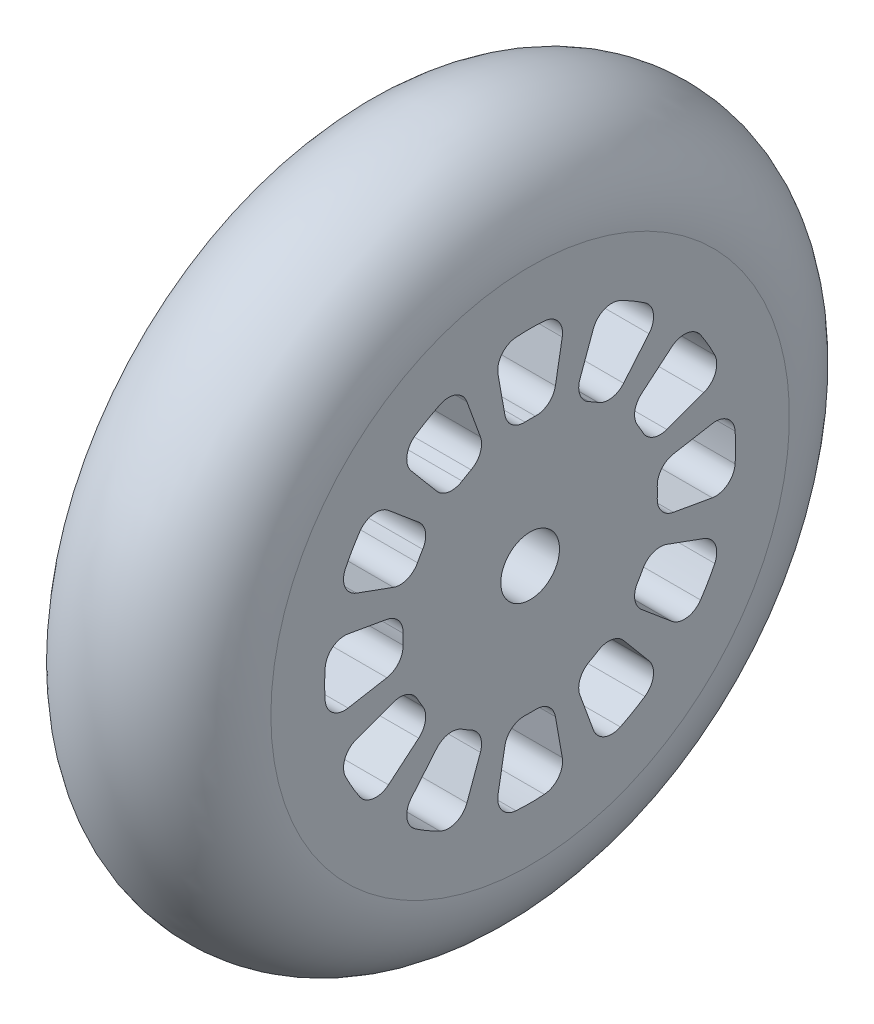
SolidWorks part; units mm, degrees
ref_plane "Front Plane" through (0, 0, 0) normal (0, 0, 1) x (1, 0, 0)
ref_plane "Top Plane" through (0, 0, 0) normal (0, 1, 0) x (1, 0, 0)
ref_plane "Right Plane" through (0, 0, 0) normal (1, 0, 0) x (0, 0, -1)
sketch "Sketch3" plane through (0, 0, 0) normal (0, 0, 1) x (1, 0, 0)
  line L0 (11.8162, 203.7798) -> (97.9345, 203.7798) construction
  line L1 (9.5, 0) -> (-9.5, 0) construction
  line L2 (9.5, 0) -> (9.5, 26.5)
  line L3 (-9.5, 26.5) -> (-9.5, 0)
  line L4 (9.5, 0) -> (-9.5, 0)
  arc A0 (9.5, 26.5) -> (-9.5, 26.5) centre (0, 26.5) ccw
  point P8 (0, 36)
  dimension "D1" = 19
  dimension "D2" = 36
ref_axis "Axis1" through (-15.0817, 0, 0) along (1, 0, 0)
revolve "Revolve1" add sketch "Sketch3" angle 360 about axis through (-15.0817, 0, 0) along (1, 0, 0)
sketch "Sketch5" plane through (0, 0, 0) normal (1, 0, 0) x (0, 0, -1)
  line L0 (42.6541, 201.0631) -> (357.9874, 201.0631) construction
  circle A0 centre (0, 0) radius 3
  dimension "D1" = 6
extrude "Cut-Extrude1" cut sketch "Sketch5" against normal up to next and the other way up to next
sketch "Sketch6" plane through (0, 0, 0) normal (1, 0, 0) x (0, 0, -1)
  line L0 (-3.6466, 20.681) -> (-2.2574, 12.8025)
  line L1 (3.6466, 20.681) -> (2.2574, 12.8025)
  line L2 (0, 21) -> (0, 13) construction
  circle A0 centre (0, 0) radius 13 construction
  circle A1 centre (0, 0) radius 21 construction
  arc A2 (-3.6466, 20.681) -> (3.6466, 20.681) centre (0, 0) cw
  arc A3 (-2.2574, 12.8025) -> (2.2574, 12.8025) centre (0, 0) cw
  dimension "D1" = 26
  dimension "D2" = 42
  dimension "D3" = 20
extrude "Cut-Extrude2" cut sketch "Sketch6" against normal through all and the other way through all
fillet "Fillet1" radius 2 4 edges at (0, 12.8025, 2.2574) (0, 12.8025, -2.2574) (0, 20.681, -3.6466) (0, 20.681, 3.6466)
pattern_circular "CirPattern2" count 12 over 360 about axis through (0, 0, 0) along (1, 0, 0) of "Fillet1", "Cut-Extrude2"
sketch "Sketch7" plane through (0, 0, 0) normal (1, 0, 0) x (0, 0, -1)
  circle A0 centre (0, 0) radius 36
  point P3 (-36, 0)
  point P4 (0, 36)
  point P5 (36, 0)
  point P6 (0, -36)
  dimension "D1" = 72
